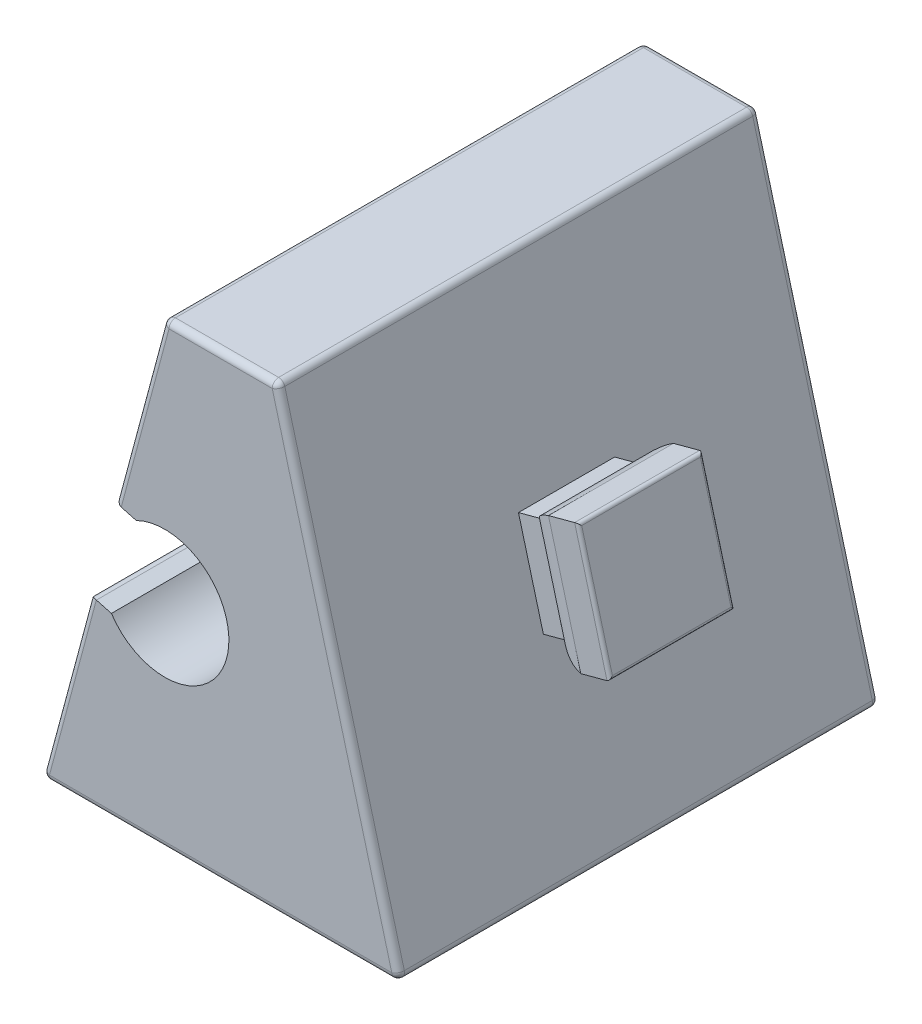
SolidWorks part; units mm, degrees
ref_plane "前视基准面" through (0, 0, 0) normal (0, 0, 1) x (1, 0, 0)
ref_plane "上视基准面" through (0, 0, 0) normal (0, 1, 0) x (1, 0, 0)
ref_plane "右视基准面" through (0, 0, 0) normal (1, 0, 0) x (0, 0, -1)
sketch "草图1" plane through (0, 0, 0) normal (0, 0, 1) x (1, 0, 0)
  line L0 (0, -7.0692) -> (0, 22.431) construction
  line L1 (-5.6, 0) -> (5.6, 0)
  line L2 (-5.6, 0) -> (-1.763, 14.32)
  line L3 (-1.763, 14.32) -> (1.763, 14.32)
  line L4 (5.6, 0) -> (1.763, 14.32)
  point P7 (0, 0)
  point P9 (0, 14.32)
extrude "凸台-拉伸1" add sketch "草图1" along normal blind 15
sketch "草图2" plane through (0, 0, 15) normal (0, 0, 1) x (1, 0, 0)
  line L1 (-1.763, 14.32) -> (-5.6, 0) construction
  line L2 (-3.6815, 7.16) -> (-4.0697, 5.7111)
  line L3 (-3.6815, 7.16) -> (-3.2933, 8.6089)
  line L4 (-4.0697, 5.7111) -> (-3.4075, 5.5337)
  line L5 (-3.2933, 8.6089) -> (-2.6312, 8.4315)
  arc A0 (-3.4075, 5.5337) -> (-2.6312, 8.4315) centre (-1.7415, 6.6403) ccw
extrude "切除-拉伸1" cut sketch "草图2" against normal blind 15
sketch "草图5" plane through (5.2249, 1.4, 0) normal (0.9659, 0.2588, 0) x (0, 0, -1)
  line L4 (-9, 7.4632) -> (-6, 7.4632)
  line L5 (-6, 7.4632) -> (-6, 4.4632)
  line L6 (-9, 7.4632) -> (-9, 4.4632)
  line L7 (-9, 4.4632) -> (-6, 4.4632)
  point P12 (-9, 5.9632)
extrude "凸台-拉伸2" add sketch "草图5" along normal blind 0.68
sketch "草图6" plane through (-1.1552, 4.3111, 0) normal (0.2588, -0.9659, 0) x (0.9659, 0.2588, 0)
  line L0 (7.9092, 5.55) -> (6.9648, 5.55)
  line L1 (6.0863, 9) -> (6.0863, 6)
  line L2 (7.9092, 5.55) -> (7.9092, 9.45)
  line L4 (7.9092, 9.45) -> (6.9648, 9.45)
  arc A0 (6.9648, 9.45) -> (6.0863, 9) centre (7.4092, 7.5) ccw
  arc A1 (6.9648, 5.55) -> (6.0863, 6) centre (7.4092, 7.5) cw
  point P1 (7.9092, 7.5)
extrude "凸台-拉伸3" add sketch "草图6" along normal blind 5 and the other way blind 5
sketch "草图7" plane through (0, 0, 9) normal (0, 0, 1) x (1, 0, 0)
  line L0 (3.4297, 10.716) -> (3.9473, 8.7841) construction
  line L3 (5.5916, 9.6906) -> (4.6794, 9.4462)
  line L4 (6.601, 5.9235) -> (5.6888, 5.6791)
  line L5 (5.1904, 11.1878) -> (5.5916, 9.6906)
  line L6 (5.1904, 11.1878) -> (7.7786, 1.5285) construction
  line L7 (6.601, 5.9235) -> (7.7786, 1.5285)
  line L8 (4.7238, 5.8864) -> (6.0179, 1.0567) construction
  line L9 (6.0179, 1.0567) -> (6.8664, 1.2841) construction
  line L10 (4.2782, 10.9434) -> (3.4297, 10.716) construction
  line L11 (6.8664, 1.2841) -> (7.7786, 1.5285) construction
  line L13 (5.1904, 11.1878) -> (4.2782, 10.9434) construction
  line L14 (3.4297, 10.716) -> (3.9473, 8.7841)
  line L16 (4.7238, 5.8864) -> (6.0179, 1.0567)
  line L17 (6.0179, 1.0567) -> (6.8664, 1.2841)
  line L18 (4.2782, 10.9434) -> (3.4297, 10.716)
  line L19 (6.8664, 1.2841) -> (7.7786, 1.5285)
  line L21 (5.1904, 11.1878) -> (4.2782, 10.9434)
  arc A0 (4.6794, 9.4462) -> (3.9473, 8.7841) centre (5.6133, 7.6776) ccw
  arc A1 (5.6888, 5.6791) -> (4.7238, 5.8864) centre (5.6133, 7.6776) cw
  point P10 (6.0963, 7.807)
extrude "切除-拉伸11" cut sketch "草图7" against normal blind 5 and the other way blind 5
fillet "圆角1" radius 0.2 16 edges at (-2.5281, 11.4644, 0) (-4.8349, 2.8556, 0) (0, 0, 0) (-5.6, 0, 7.5) (-4.0697, 5.7111, 7.5) (-3.2933, 8.6089, 7.5) (5.6, 0, 7.5) (0, 0, 15) (-4.8349, 2.8556, 15) (-2.5281, 11.4644, 15) (3.6815, 7.16, 15) (3.6815, 7.16, 0) (0, 14.32, 0) (-1.763, 14.32, 7.5) (1.763, 14.32, 7.5) (0, 14.32, 15)
fillet "圆角5" radius 0.1 4 edges at (6.601, 5.9235, 7.5) (6.0963, 7.807, 5.55) (5.5916, 9.6906, 7.5) (6.0963, 7.807, 9.45)
